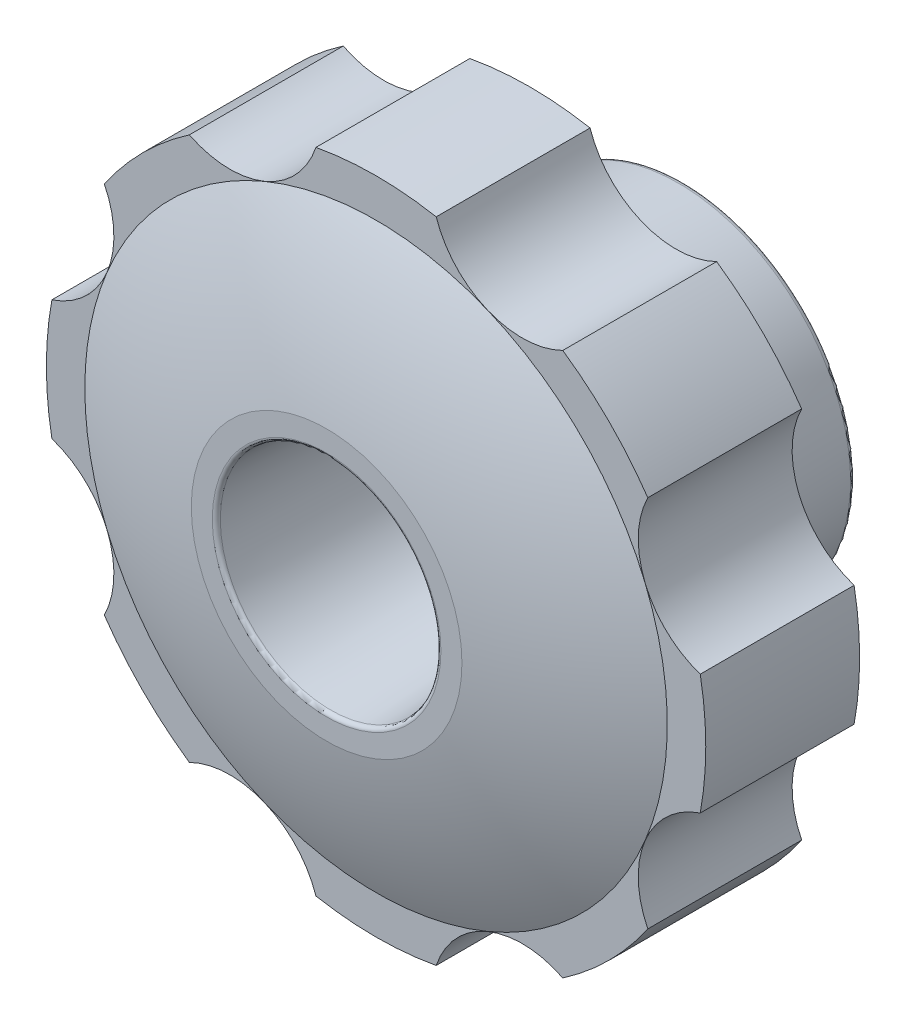
SolidWorks part; units mm, degrees
ref_plane "Front Plane" through (0, 0, 0) normal (0, 0, 1) x (1, 0, 0)
ref_plane "Top Plane" through (0, 0, 0) normal (0, 1, 0) x (1, 0, 0)
ref_plane "Right Plane" through (0, 0, 0) normal (1, 0, 0) x (0, 0, -1)
sketch "SK_C1_profile" plane through (0, 0, 0) normal (0, 1, 0) x (1, 0, 0)
  line L0 (0, 17.272) -> (15.3929, 17.272)
  line L1 (15.9002, 16.7906) -> (16.6204, 3.048)
  line L2 (16.6204, 3.048) -> (30.48, 3.048)
  line L3 (30.48, 3.048) -> (30.48, -11.176)
  line L4 (30.48, -11.176) -> (26.924, -11.176)
  line L5 (12.5108, -15.748) -> (0, -15.748)
  line L6 (0, -15.748) -> (0, 17.272)
  line L7 (0, 50.8) -> (0, -50.8) construction
  arc A0 (15.3929, 17.272) -> (15.9002, 16.7906) centre (15.3929, 16.764) cw
  arc A1 (26.924, -11.176) -> (12.5108, -15.748) centre (3.1639, 38.7226) cw
revolve "C1_MainRevolve" add sketch "SK_C1_profile" angle 360 about L7
ref_plane "Z=-0.12000" through (0, 0, -3.048) normal (0, 0, 1) x (1, 0, 0)
sketch "SK_C3_Lci" plane through (0, 0, -3.048) normal (0, 0, 1) x (1, 0, 0)
  arc A0 (27.7697, -4.8728) -> (27.7697, 4.8728) centre (0, 0) ccw
  arc A1 (27.7697, 4.8728) -> (23.0818, 16.1905) centre (32.6185, 13.511) cw
  arc A2 (23.0818, 16.1905) -> (16.1905, 23.0818) centre (0, 0) ccw
  arc A3 (16.1905, 23.0818) -> (4.8728, 27.7697) centre (13.511, 32.6185) cw
  arc A4 (4.8728, 27.7697) -> (-4.8728, 27.7697) centre (0, 0) ccw
  arc A5 (-4.8728, 27.7697) -> (-16.1905, 23.0818) centre (-13.511, 32.6185) cw
  arc A6 (-16.1905, 23.0818) -> (-23.0818, 16.1905) centre (0, 0) ccw
  arc A7 (-23.0818, 16.1905) -> (-27.7697, 4.8728) centre (-32.6185, 13.511) cw
  arc A8 (-27.7697, 4.8728) -> (-27.7697, -4.8728) centre (0, 0) ccw
  arc A9 (-27.7697, -4.8728) -> (-23.0818, -16.1905) centre (-32.6185, -13.511) cw
  arc A10 (-23.0818, -16.1905) -> (-16.1905, -23.0818) centre (0, 0) ccw
  arc A11 (-16.1905, -23.0818) -> (-4.8728, -27.7697) centre (-13.511, -32.6185) cw
  arc A12 (-4.8728, -27.7697) -> (4.8728, -27.7697) centre (0, 0) ccw
  arc A13 (4.8728, -27.7697) -> (16.1905, -23.0818) centre (13.511, -32.6185) cw
  arc A14 (16.1905, -23.0818) -> (23.0818, -16.1905) centre (0, 0) ccw
  arc A15 (23.0818, -16.1905) -> (27.7697, -4.8728) centre (32.6185, -13.511) cw
extrude "C3a_CavityPrism" cut sketch "SK_C3_Lci" along normal blind 11.938
sketch "SK_C3_ceiling" plane through (0, 0, 0) normal (0, 1, 0) x (1, 0, 0)
  line L0 (25.654, -6.604) -> (23.368, -8.89)
  line L1 (23.368, -8.89) -> (30.48, -8.89)
  line L2 (30.48, -8.89) -> (30.48, -6.604)
  line L3 (30.48, -6.604) -> (25.654, -6.604)
  line L4 (0, 50.8) -> (0, -50.8) construction
revolve "C3b_CeilingRing" add sketch "SK_C3_ceiling" angle 360 about L4
sketch "SK_C3_hub" plane through (0, 0, 0) normal (0, 1, 0) x (1, 0, 0)
  line L0 (0, 3.048) -> (16.6204, 3.048)
  line L1 (16.6204, 3.048) -> (17.2461, -8.89)
  line L2 (17.2461, -8.89) -> (0, -8.89)
  line L3 (0, -8.89) -> (0, 3.048)
  line L4 (0, 50.8) -> (0, -50.8) construction
revolve "C3c_HubUp" add sketch "SK_C3_hub" angle 360 about L4
sketch "SK_C3_ribs" plane through (0, 0, -3.048) normal (0, 0, 1) x (1, 0, 0)
  line L0 (10.16, -0.635) -> (29.21, -0.635)
  line L1 (29.21, -0.635) -> (29.21, 0.635)
  line L2 (29.21, 0.635) -> (10.16, 0.635)
  line L3 (10.16, 0.635) -> (10.16, -0.635)
  line L4 (7.6332, 6.7352) -> (21.1036, 20.2056)
  line L5 (21.1036, 20.2056) -> (20.2056, 21.1036)
  line L6 (20.2056, 21.1036) -> (6.7352, 7.6332)
  line L7 (6.7352, 7.6332) -> (7.6332, 6.7352)
  line L8 (0.635, 10.16) -> (0.635, 29.21)
  line L9 (0.635, 29.21) -> (-0.635, 29.21)
  line L10 (-0.635, 29.21) -> (-0.635, 10.16)
  line L11 (-0.635, 10.16) -> (0.635, 10.16)
  line L12 (-6.7352, 7.6332) -> (-20.2056, 21.1036)
  line L13 (-20.2056, 21.1036) -> (-21.1036, 20.2056)
  line L14 (-21.1036, 20.2056) -> (-7.6332, 6.7352)
  line L15 (-7.6332, 6.7352) -> (-6.7352, 7.6332)
  line L16 (-10.16, 0.635) -> (-29.21, 0.635)
  line L17 (-29.21, 0.635) -> (-29.21, -0.635)
  line L18 (-29.21, -0.635) -> (-10.16, -0.635)
  line L19 (-10.16, -0.635) -> (-10.16, 0.635)
  line L20 (-7.6332, -6.7352) -> (-21.1036, -20.2056)
  line L21 (-21.1036, -20.2056) -> (-20.2056, -21.1036)
  line L22 (-20.2056, -21.1036) -> (-6.7352, -7.6332)
  line L23 (-6.7352, -7.6332) -> (-7.6332, -6.7352)
  line L24 (-0.635, -10.16) -> (-0.635, -29.21)
  line L25 (-0.635, -29.21) -> (0.635, -29.21)
  line L26 (0.635, -29.21) -> (0.635, -10.16)
  line L27 (0.635, -10.16) -> (-0.635, -10.16)
  line L28 (6.7352, -7.6332) -> (20.2056, -21.1036)
  line L29 (20.2056, -21.1036) -> (21.1036, -20.2056)
  line L30 (21.1036, -20.2056) -> (7.6332, -6.7352)
  line L31 (7.6332, -6.7352) -> (6.7352, -7.6332)
extrude "C3d_Ribs" add sketch "SK_C3_ribs" along normal blind 11.938
sketch "SK_C2_scallops" plane through (0, 0, 0) normal (0, 0, 1) x (1, 0, 0)
  circle A0 centre (32.6185, 13.511) radius 8.382
  circle A1 centre (13.511, 32.6185) radius 8.382
  circle A2 centre (-13.511, 32.6185) radius 8.382
  circle A3 centre (-32.6185, 13.511) radius 8.382
  circle A4 centre (-32.6185, -13.511) radius 8.382
  circle A5 centre (-13.511, -32.6185) radius 8.382
  circle A6 centre (13.511, -32.6185) radius 8.382
  circle A7 centre (32.6185, -13.511) radius 8.382
extrude "C2_Scallops" cut sketch "SK_C2_scallops" along normal through all and the other way through all
sketch "SK_C4_bore" plane through (0, 0, 0) normal (0, 1, 0) x (1, 0, 0)
  line L0 (0, 18.542) -> (6.7469, 18.542)
  line L1 (6.7469, 18.542) -> (6.7469, 4.572)
  line L2 (6.7469, 4.572) -> (9.144, 4.572)
  line L3 (9.144, 4.572) -> (10.19, -15.3869)
  line L4 (10.5705, -15.748) -> (10.5705, -18.288)
  line L5 (10.5705, -18.288) -> (0, -18.288)
  line L6 (0, -18.288) -> (0, 18.542)
  line L7 (0, 50.8) -> (0, -50.8) construction
  arc A0 (10.19, -15.3869) -> (10.5705, -15.748) centre (10.5705, -15.367) ccw
revolve "C4_Bore" cut sketch "SK_C4_bore" angle 360 about L7
sketch "SK_C5_ridge" plane through (0, 0, 0) normal (0, 1, 0) x (1, 0, 0)
  line L0 (9.7896, 17.653) -> (12.8323, 17.653)
  line L1 (12.8323, 17.653) -> (12.8323, 17.272)
  line L2 (12.8323, 17.272) -> (9.7896, 17.272)
  line L3 (9.7896, 17.272) -> (9.7896, 17.653)
  line L4 (0, 50.8) -> (0, -50.8) construction
revolve "C5_Ridge" add sketch "SK_C5_ridge" angle 360 about L4
equation "\"Z_hub_end\" = -0.680000in"
equation "\"R_hub_end\" = 0.625000in"
equation "\"hub_draft_deg\" = 3.000000"
equation "\"R_hub_end_round\" = 0.020000in"
equation "\"Z_underside\" = -0.120000in"
equation "\"R_head\" = 1.200000in"
equation "\"Z_rim_top\" = 0.440000in"
equation "\"R_top_flat_in\" = 1.060000in"
equation "\"R_dome\" = 2.175763in"
equation "\"Dome_cx\" = 0.124593in"
equation "\"Dome_cz\" = -1.524424in"
equation "\"R_top_face_out\" = 0.492553in"
equation "\"Z_top\" = 0.620000in"
equation "\"R_scallop_pcd\" = 1.390000in"
equation "\"R_scallop\" = 0.330000in"
equation "\"N_lobes\" = 8.000000"
equation "\"R_rim_in\" = 1.110000in"
equation "\"R_scallop_in\" = 0.390000in"
equation "\"Z_step\" = 0.260000in"
equation "\"Z_ceiling\" = 0.350000in"
equation "\"R_step\" = 1.010000in"
equation "\"R_ceiling\" = 0.920000in"
equation "\"T_rib\" = 0.050000in"
equation "\"R_seat\" = 0.265625in"
equation "\"Z_seat_top\" = -0.180000in"
equation "\"R_bore_bot\" = 0.360000in"
equation "\"bore_taper_deg\" = 3.000000"
equation "\"R_bore_round\" = 0.015000in"
equation "\"R_ridge_in\" = 0.385417in"
equation "\"R_ridge_out\" = 0.505208in"
equation "\"H_ridge\" = 0.015000in"
